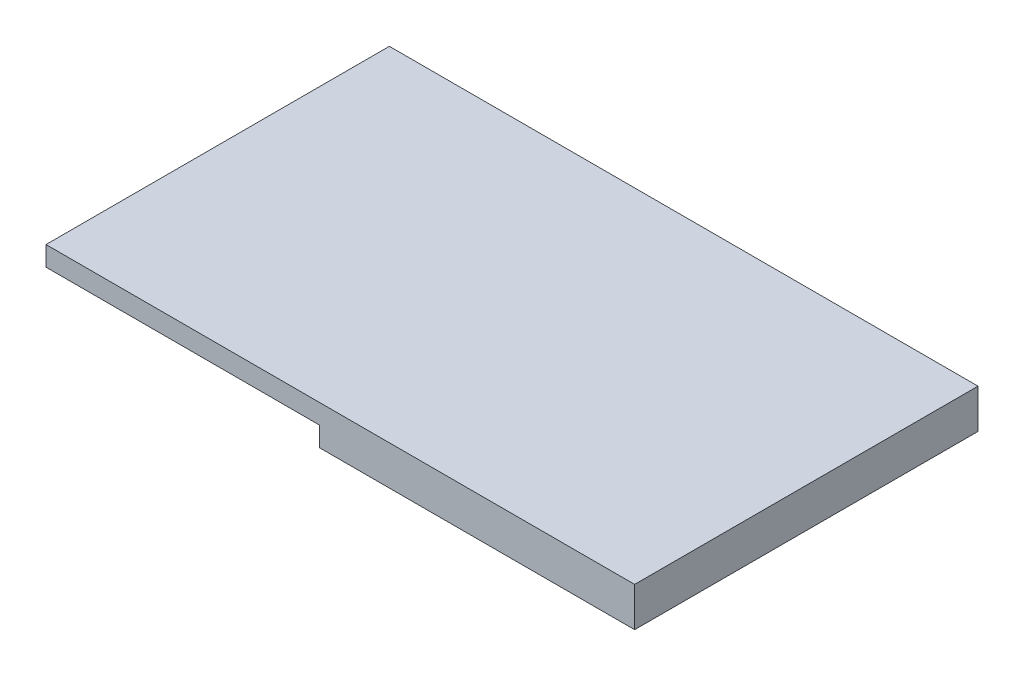
SolidWorks part; units mm, degrees
ref_plane "Front Plane" through (0, 0, 0) normal (0, 0, 1) x (1, 0, 0)
ref_plane "Top Plane" through (0, 0, 0) normal (0, 1, 0) x (1, 0, 0)
ref_plane "Right Plane" through (0, 0, 0) normal (1, 0, 0) x (0, 0, -1)
sketch "Sketch1" plane through (0, 0, 0) normal (0, 1, 0) x (1, 0, 0)
  line L1 (-30, 17.5) -> (30, 17.5)
  line L2 (-30, 17.5) -> (-30, -17.5)
  line L3 (-30, -17.5) -> (30, -17.5)
  line L4 (30, 17.5) -> (30, -17.5)
  line L5 (-30, 17.5) -> (30, -17.5) construction
  line L6 (-30, -17.5) -> (30, 17.5) construction
  point P0 (0, 0)
extrude "Boss-Extrude1" add sketch "Sketch1" along normal blind 4
sketch "Sketch2" plane through (0, 0, 0) normal (0, -1, 0) x (1, 0, 0)
  line L0 (30, -17.5) -> (-30, -17.5) construction
  line L1 (-30, 17.5) -> (-2.1146, 17.5)
  line L2 (-30, 17.5) -> (-30, -17.5)
  line L3 (-30, -17.5) -> (-2.1146, -17.5)
  line L4 (-2.1146, 17.5) -> (-2.1146, -17.5)
  line L5 (-2.1146, 19.5412) -> (-2.1146, -20.4588) construction
extrude "Cut-Extrude1" cut sketch "Sketch2" against normal blind 2
